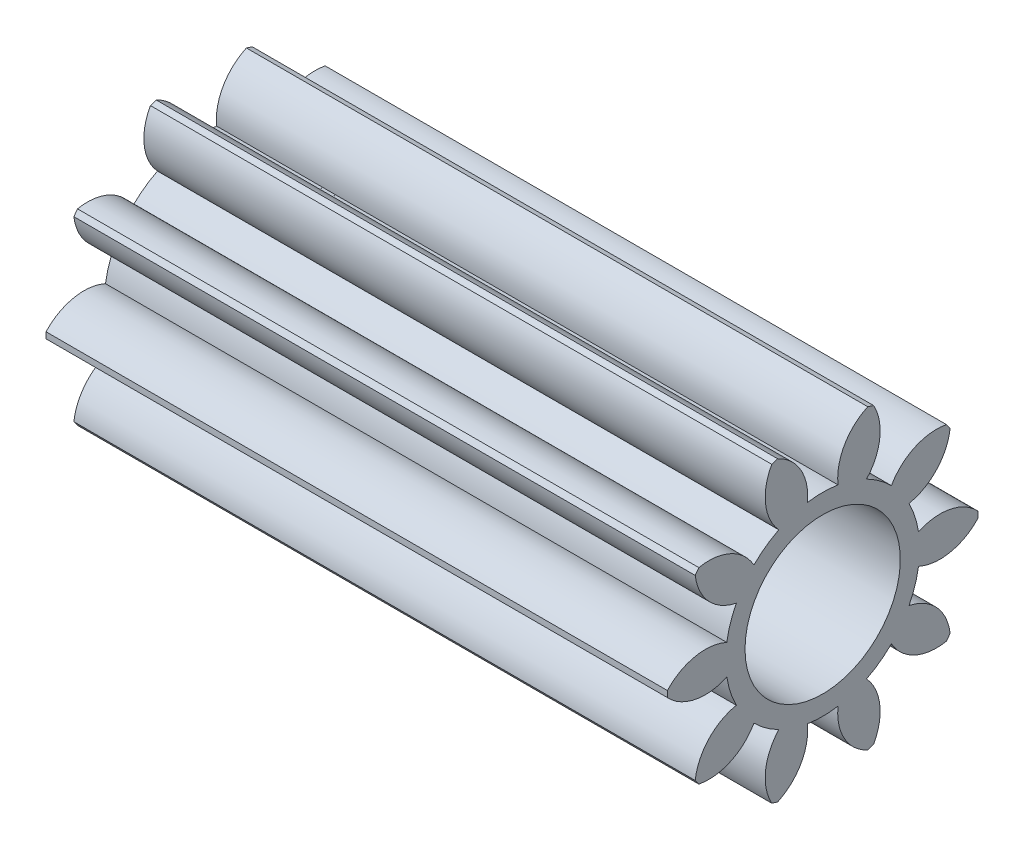
SolidWorks part; units mm, degrees
ref_plane "Plane1" through (0, 0, 0) normal (0, 0, 1) x (1, 0, 0)
ref_plane "Plane2" through (0, 0, 0) normal (0, 1, 0) x (1, 0, 0)
ref_plane "Plane3" through (0, 0, 0) normal (1, 0, 0) x (0, 0, -1)
sketch "HoldingSke" plane through (0, 0, 0) normal (0, 1, 0) x (1, 0, 0)
  line L0 (0, 0) -> (1.9696, -0.3473)
  line L1 (-15, 0) -> (100, 0) construction
  line L2 (0, 0) -> (-2.1039, 2.3779)
  line L3 (0, 0) -> (-11.863, 4.5341)
  line L4 (0, 0) -> (8.5048, 1.4996)
  line L5 (0, 0) -> (-46.8476, -17.4728)
  line L6 (0, 0) -> (-9.9476, -6.7116)
  line L7 (-2.1039, 2.3779) -> (8.6586, 51.2059)
  line L8 (-76.2, 54.61) -> (-75.7, 54.61)
  line L9 (-71.009, 38.7566) -> (-53.1078, 45.2721)
  line L10 (-76.2, 71.12) -> (104.1128, 71.12)
  line L11 (0, 0) -> (-12, 0)
  line L12 (-76.2, 101.6) -> (-76.181, 101.6)
  line L13 (24.9733, 27.94) -> (52.9518, 28.4284)
  line L14 (24.9733, 27.94) -> (24.9743, 27.94)
  line L15 (24.9733, 27.94) -> (100.4006, 29.5858)
  line L16 (-63.627, -0.5) -> (-12.827, -0.5)
  circle A0 centre (0, 0) radius 1.5
  circle A1 centre (0, 0) radius 1.874
  circle A2 centre (0, 0) radius 37.5
  circle A3 centre (0, 0) radius 1.5
  dimension "MHD" = 3.748
  dimension "Hub_dia" = 75
  dimension "Bore" = 3
  dimension "MBD" = 3
  dimension "Num_teeth" = 10
  dimension "Pitch" = 2
  dimension "Overall_len" = 50
  dimension "Show_teeth" = 10
  dimension "Thickness" = 12
  dimension "OAL" = 50.0001
  dimension "T_dim" = 0.5
  dimension "Ap" = 20
  dimension "H" = 19.05
  dimension "Pitch_radius" = 180.3128
  dimension "Width" = 12
  dimension "Backlash" = 0.019
  dimension "Addendum_fac" = 1
  dimension "Dedendum_fac" = 1.25
  dimension "Clearance_fac" = 0.25
  dimension "Dedendum_add" = 0.001
  dimension "Module" = 0.5
sketch "BasProSke" plane through (0, 0, 0) normal (0, 1, 0) x (1, 0, 0)
  line L0 (-10, 0) -> (60, 0) construction
  line L1 (0, 0) -> (0, 3)
  line L2 (0, 0) -> (12, 0)
  line L3 (12, 0) -> (12, 3)
  line L4 (12, 3) -> (0, 3)
  dimension "Thickness" = 12
  dimension "Diameter" = 6
revolve "Base-Revolve" add sketch "BasProSke" angle 360 about L0
sketch "TooCutSke" plane through (0, 0, 0) normal (1, 0, 0) x (0, 0, -1)
  line L1 (0, 0) -> (0, 107) construction
  line L2 (0, 0) -> (-0.4243, 2.4637) construction
  line L3 (0, 0) -> (-1.5292, 4.7063) construction
  line L4 (-0.4243, 2.4637) -> (-0.7646, 2.3532) construction
  arc A0 (0.2964, 1.8504) -> (-0.2964, 1.8504) centre (0, 0) ccw
  arc A1 (0.9059, 2.8866) -> (-0.9059, 2.8866) centre (0, 0) ccw
  circle A2 centre (0, 0) radius 2.5 construction
  circle A3 centre (0, 0) radius 2.3492 construction
  arc A4 (-0.2964, 1.8504) -> (-0.9059, 2.8866) centre (-1.2901, 1.9633) ccw
  arc A5 (0.9059, 2.8866) -> (0.2964, 1.8504) centre (1.2901, 1.9633) ccw
  dimension "Root_dia" = 3.748
  dimension "Overcut_dia" = 6.0508
  dimension "Pitch_dia" = 5
  dimension "Base_dia" = 4.6985
  dimension "Flank_rad" = 1
  dimension "Half_ang" = 18
  dimension "Half_CT" = 0.3578
extrude "ToothCut" cut sketch "TooCutSke" along normal through all
fillet "Breaks" [suppressed] radius 0.01
fillet "RootFillets" [suppressed] radius 0.126
pattern_circular "TeethCuts" count 10 every 36 about axis through (-10, 0, 0) along (1, 0, 0) of "ToothCut", "RootFillets", "Breaks"
sketch "HubNeaOneSke" plane through (0, 0, 0) normal (-1, 0, 0) x (0, 0, 1)
  circle A0 centre (0, 0) radius 1.874
  dimension "Diameter" = 3.748
extrude "HubNearOne" [suppressed] add sketch "HubNeaOneSke" along normal blind 38.0001
sketch "HubNeaBotSke" plane through (0, 0, 0) normal (-1, 0, 0) x (0, 0, 1)
  circle A0 centre (0, 0) radius 1.874
  dimension "Diameter" = 3.748
extrude "HubNearBoth" [suppressed] add sketch "HubNeaBotSke" along normal blind 19
ref_plane "FarPln" through (12, 0, 0) normal (1, 0, 0) x (0, 0, -1)
sketch "HubFarSke" plane through (12, 0, 0) normal (1, 0, 0) x (0, 0, -1)
  circle A0 centre (0, 0) radius 1.874
  dimension "Diameter" = 3.748
extrude "HubFar" [suppressed] add sketch "HubFarSke" along normal blind 19
sketch "BorSke" plane through (0, 0, 0) normal (1, 0, 0) x (0, 0, -1)
  circle A0 centre (0, 0) radius 1.5
  dimension "Diameter" = 3
extrude "Bore" cut sketch "BorSke" along normal mid plane 100.0001
sketch "KeySke" plane through (0, 0, 0) normal (1, 0, 0) x (0, 0, -1)
  line L0 (-0.6, 0) -> (-0.6, 2)
  line L1 (-0.6, 2) -> (0.6, 2)
  line L2 (0.6, 2) -> (0.6, 0)
  line L3 (0, 0) -> (0, 34) construction
  line L4 (-0.6, 0) -> (0.6, 0)
  dimension "Offset" = 2
extrude "Keyway" [suppressed] cut sketch "KeySke" along normal mid plane 100.0001
pattern_circular "Keyway2" [suppressed] count 2 every 90 about axis through (-10, 0, 0) along (1, 0, 0)
equation "' \"Module@HoldingSke\" = 6.35"
equation "' \"Num_teeth@HoldingSke\" = 12"
equation "' \"Ap@HoldingSke\" =  20"
equation "' \"Ap@HoldingSke\" = 20"
equation "' \"Width@HoldingSke\" = 0.5 * 25.4"
equation "' \"Hub_dia@HoldingSke\"= 1 * 25.4"
equation "' \"Hub_dia@HoldingSke\" = 1 * 25.4"
equation "' \"Overall_len@HoldingSke\" = 1.0 * 25.4"
equation "' \"Bore@HoldingSke\" = 0.75 * 25.4"
equation "' \"T_dim@HoldingSke\" = 0.1 * 25.4"
equation "' \"Width@KeySke\" = 0.25 * 25.4"
equation "' \"Show_teeth@HoldingSke\" = 13"
equation "' \"Backlash@HoldingSke\" = 0.009 * 25.4"
equation "' \"Addendum_fac@HoldingSke\" = 1.0"
equation "' \"Dedendum_fac@HoldingSke\" = 1.25"
equation "' \"Dedendum_add@HoldingSke\" = 0.00005 * 25.4"
equation "' \"Clearance_fac@HoldingSke\" = 0.25"
equation "\"Pitch@HoldingSke\" = 1 / \"Module@HoldingSke\""
equation "\"Overcut_dia@TooCutSke\" = (\"Num_teeth@HoldingSke\" + 2 * \"Addendum_fac@HoldingSke\") / \"Pitch@HoldingSke\" + 0.002 * 25.4"
equation "\"Pitch_dia@TooCutSke\" = \"Num_teeth@HoldingSke\" / \"Pitch@HoldingSke\""
equation "\"Base_dia@TooCutSke\" = \"Num_teeth@HoldingSke\" / \"Pitch@HoldingSke\" * cos((\"Ap@HoldingSke\"  * 3.14159265 / 180))"
equation "\"Root_dia@TooCutSke\" = (\"Num_teeth@HoldingSke\" + 2) / \"Pitch@HoldingSke\" - 2 * (\"Addendum_fac@HoldingSke\" + \"Dedendum_fac@HoldingSke\") / \"Pitch@HoldingSke\" - \"Dedendum_add@HoldingSke\" * 2"
equation "\"Half_ang@TooCutSke\" = 180 / \"Num_teeth@HoldingSke\""
equation "\"Half_CT@TooCutSke\" = \"Num_teeth@HoldingSke\" / \"Pitch@HoldingSke\" * sin((3.14159265 / 2 / \"Num_teeth@HoldingSke\")) / 2 - 7 * \"Backlash@HoldingSke\" / 4"
equation "\"Flank_rad@TooCutSke\" = \"Num_teeth@HoldingSke\" / \"Pitch@HoldingSke\" / 5"
equation "\"Radius@RootFillets\" = \"Clearance_fac@HoldingSke\" / \"Pitch@HoldingSke\" + \"Dedendum_add@HoldingSke\""
equation "\"Break_rad@Breaks\" = 0.02 / \"Pitch@HoldingSke\""
equation "\"Thickness@HoldingSke\" = \"Width@HoldingSke\""
equation "\"OAL@HoldingSke\" = \"Thickness@HoldingSke\""
equation "\"MHD@HoldingSke\" = (\"Num_teeth@HoldingSke\" + 2) / \"Pitch@HoldingSke\" - 2 * (\"Addendum_fac@HoldingSke\" + \"Dedendum_fac@HoldingSke\")  / \"Pitch@HoldingSke\" - \"Dedendum_add@HoldingSke\" * 2"
equation "\"MBD@HoldingSke\" = (\"Num_teeth@HoldingSke\" + 2) / \"Pitch@HoldingSke\" - 2 * (\"Addendum_fac@HoldingSke\" + \"Dedendum_fac@HoldingSke\")  / \"Pitch@HoldingSke\" - \"Dedendum_add@HoldingSke\" * 2 - 0.002 * 25.4"
equation "\"MHD@HoldingSke\" = ((sgn( \"MHD@HoldingSke\" - \"Hub_dia@HoldingSke\" )-1)*( \"MHD@HoldingSke\" - \"Hub_dia@HoldingSke\" ))/-2+ \"Hub_dia@HoldingSke\""
equation "\"MBD@HoldingSke\" = ((sgn( \"MBD@HoldingSke\" - \"Bore@HoldingSke\" )-1)*( \"MBD@HoldingSke\" - \"Bore@HoldingSke\" ))/-2+ \"Bore@HoldingSke\""
equation "\"OAL@HoldingSke\" = ((sgn( \"OAL@HoldingSke\" - \"Overall_len@HoldingSke\" )+1)*( \"OAL@HoldingSke\" - \"Overall_len@HoldingSke\" ))/2 + \"Overall_len@HoldingSke\" + 0.000002 * 25.4"
equation "\"Num_teeth@TeethCuts\" = int( \"Show_teeth@HoldingSke\" ) + 1"
equation "\"Num_teeth@TeethCuts\" = ((sgn( \"Num_teeth@TeethCuts\" - \"Num_teeth@HoldingSke\" )-1)*( \"Num_teeth@TeethCuts\" - \"Num_teeth@HoldingSke\" ))/-2+ \"Num_teeth@HoldingSke\""
equation "\"Num_teeth@TeethCuts\" = ((sgn( \"Num_teeth@TeethCuts\" - 2.0)+1)*( \"Num_teeth@TeethCuts\" - 2.0))/2 +2.0"
equation "\"Angle@TeethCuts\" = 360.0 / \"Num_teeth@HoldingSke\""
equation "\"Diameter@BasProSke\" = (\"Num_teeth@HoldingSke\" + 2 * \"Addendum_fac@HoldingSke\") / \"Pitch@HoldingSke\""
equation "\"Thickness@BasProSke\"  = \"Thickness@HoldingSke\""
equation "' \"Fillet_rad@BasProSke\" =  \"Thickness@HoldingSke\" * 0.05"
equation "' \"Fillet_rad@BasProSke\" = \"Thickness@HoldingSke\" * 0.05"
equation "\"MHD@HoldingSke\" = ((sgn( \"MHD@HoldingSke\" - \"Root_dia@TooCutSke\" )-1)*( \"MHD@HoldingSke\" - \"Root_dia@TooCutSke\" ))/-2+ \"Root_dia@TooCutSke\""
equation "\"Diameter@HubNeaOneSke\" = \"MHD@HoldingSke\""
equation "\"Length@HubNearOne\" = \"OAL@HoldingSke\" - \"Thickness@BasProSke\""
equation "\"Diameter@HubNeaBotSke\" = \"MHD@HoldingSke\""
equation "\"Length@HubNearBoth\" = ( \"OAL@HoldingSke\" - \"Thickness@BasProSke\" ) / 2.0"
equation "\"Thickness@FarPln\" = \"Thickness@BasProSke\""
equation "\"Diameter@HubFarSke\" = \"MHD@HoldingSke\""
equation "\"Length@HubFar\" = ( \"OAL@HoldingSke\" - \"Thickness@BasProSke\" ) / 2.0"
equation "\"Diameter@BorSke\" = \"MBD@HoldingSke\""
equation "\"D1@Bore\" = \"OAL@HoldingSke\" * 2.0"
equation "\"D1@Keyway\" = \"OAL@HoldingSke\" * 2.0"
equation "\"Offset@KeySke\" = \"T_dim@HoldingSke\" + \"MBD@HoldingSke\" / 2.0"
